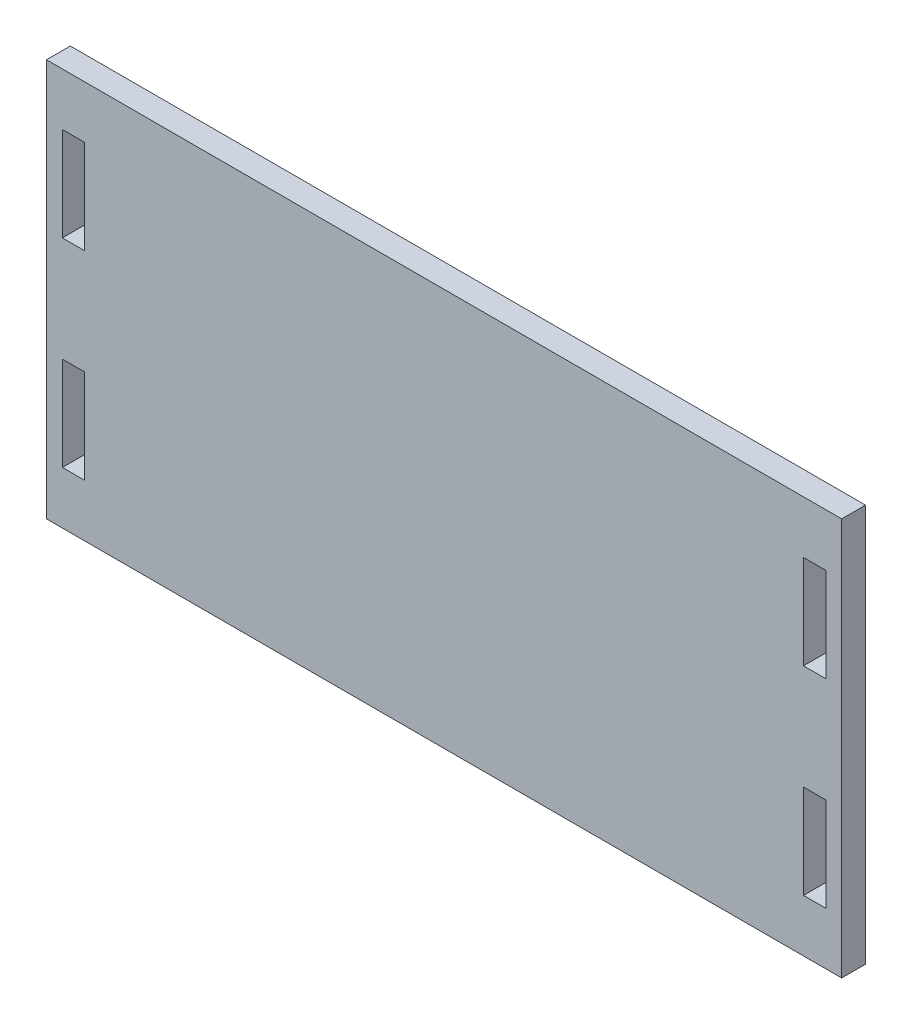
SolidWorks part; units mm, degrees
ref_plane "Спереди" through (0, 0, 0) normal (0, 0, 1) x (1, 0, 0)
ref_plane "Сверху" through (0, 0, 0) normal (0, 1, 0) x (1, 0, 0)
ref_plane "Справа" through (0, 0, 0) normal (1, 0, 0) x (0, 0, -1)
sketch "Эскиз1" plane through (0, 0, 0) normal (0, 0, 1) x (1, 0, 0)
  line L0 (50, 50) -> (50, 0) construction
  line L1 (0, 0) -> (100, 0)
  line L2 (0, 0) -> (0, 50)
  line L3 (0, 50) -> (100, 50)
  line L4 (100, 0) -> (100, 50)
  line L5 (2, 43.4) -> (4.8, 43.4)
  line L6 (2, 43.4) -> (2, 31.6)
  line L7 (2, 31.6) -> (4.8, 31.6)
  line L8 (4.8, 43.4) -> (4.8, 31.6)
  line L9 (0, 25) -> (100, 25) construction
  line L10 (4.8, 37.5) -> (50, 37.5) construction
  line L11 (2, 18.4) -> (4.8, 18.4)
  line L12 (4.8, 6.6) -> (4.8, 18.4)
  line L13 (2, 6.6) -> (4.8, 6.6)
  line L14 (2, 6.6) -> (2, 18.4)
  line L15 (98, 6.6) -> (98, 18.4)
  line L16 (98, 6.6) -> (95.2, 6.6)
  line L17 (95.2, 6.6) -> (95.2, 18.4)
  line L18 (98, 18.4) -> (95.2, 18.4)
  line L19 (98, 31.6) -> (95.2, 31.6)
  line L20 (95.2, 43.4) -> (95.2, 31.6)
  line L21 (98, 43.4) -> (95.2, 43.4)
  line L22 (98, 43.4) -> (98, 31.6)
  dimension "D1" = 100
  dimension "D2" = 50
  dimension "D3" = 2.8
  dimension "D4" = 11.8
  dimension "D5" = 2
  dimension "D6" = 12.5
extrude "Бобышка-Вытянуть1" add sketch "Эскиз1" against normal blind 3
